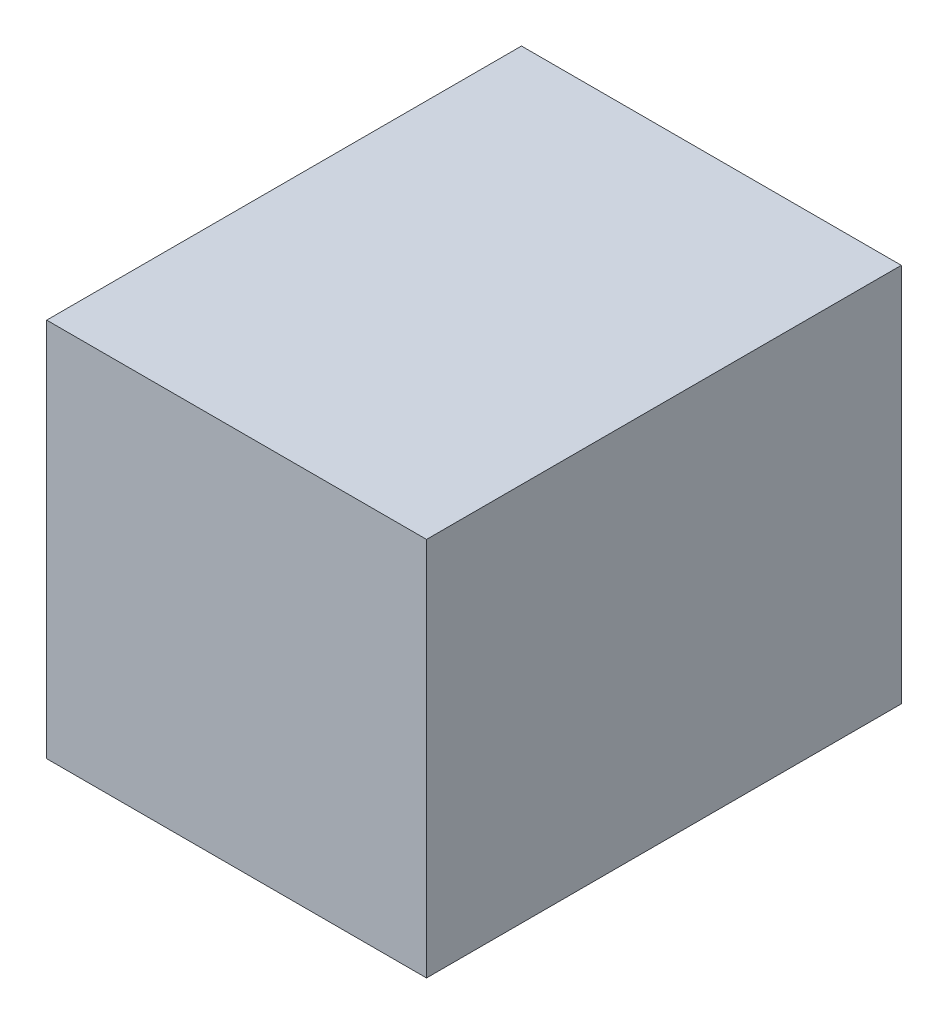
SolidWorks part; units mm, degrees
ref_plane "Front Plane" through (0, 0, 0) normal (0, 0, 1) x (1, 0, 0)
ref_plane "Top Plane" through (0, 0, 0) normal (0, 1, 0) x (1, 0, 0)
ref_plane "Right Plane" through (0, 0, 0) normal (1, 0, 0) x (0, 0, -1)
sketch "Sketch1" plane through (0, 0, 0) normal (0, 1, 0) x (1, 0, 0)
  line L1 (0, 0) -> (0.8, 0)
  line L2 (0, 0) -> (0, 1)
  line L3 (0, 1) -> (0.8, 1)
  line L4 (0.8, 0) -> (0.8, 1)
extrude "Boss-Extrude1" add sketch "Sketch1" along normal blind 0.8
